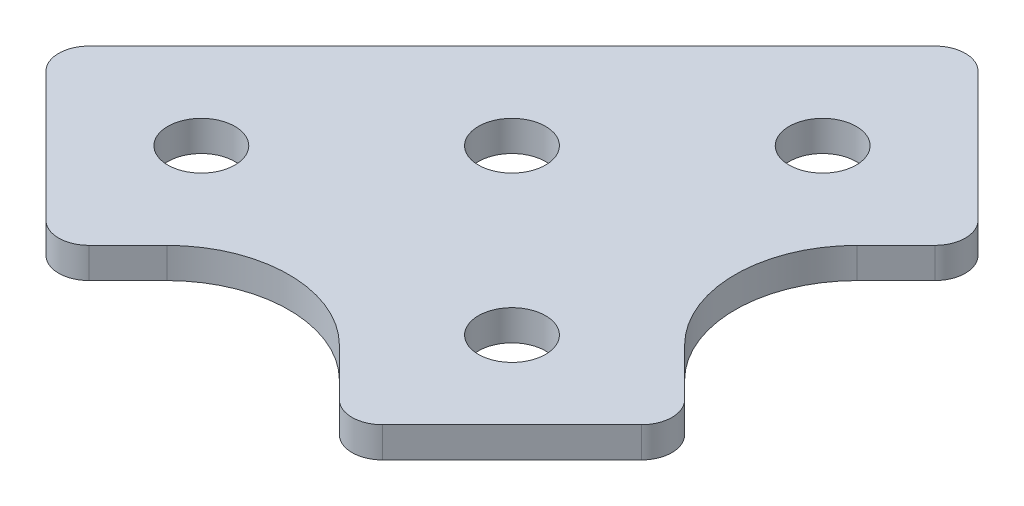
SolidWorks part; units mm, degrees
material "5052-H32"
ref_plane "Front Plane" through (0, 0, 0) normal (0, 0, 1) x (1, 0, 0)
ref_plane "Top Plane" through (0, 0, 0) normal (0, 1, 0) x (1, 0, 0)
ref_plane "Right Plane" through (0, 0, 0) normal (1, 0, 0) x (0, 0, -1)
sketch "Sketch1" plane through (0, 0, 0) normal (0, 1, 0) x (1, 0, 0)
  line L0 (-17.9605, 17.9605) -> (0, 35.921)
  line L5 (32.3289, -32.3289) -> (0, 0)
  line L6 (32.3289, -32.3289) -> (50.2894, -14.3684)
  line L7 (50.2894, -14.3684) -> (17.9605, 17.9605)
  line L9 (0, 0) -> (-31.4309, -31.4309)
  line L11 (-17.9605, 17.9605) -> (-49.3914, -13.4704)
  line L12 (-31.4309, -31.4309) -> (-49.3914, -13.4704)
  line L13 (0, 35.921) -> (17.9605, 17.9605)
  line L14 (-17.9605, 17.9605) -> (0, 0) construction
  line L15 (17.9605, 17.9605) -> (0, 0) construction
  line L16 (0, 0) -> (0, 35.921) construction
  point P3 (0, 17.9605)
  dimension "D1" = 25.4
  dimension "D2" = 25.4
  dimension "D5" = 90
  dimension "D4" = 45.72
  dimension "D3" = 57.15
extrude "Boss-Extrude1" add sketch "Sketch1" along normal blind 3.175 contours L0 L13 L7 L6 L5 L9 L12 L11
sketch "Sketch2" plane through (0, 3.175, 0) normal (0, 1, 0) x (1, 0, 0)
  line L0 (-49.3914, -13.4704) -> (-31.4309, -31.4309) construction
  line L1 (-32.3289, -14.3684) -> (-40.4112, -22.4506) construction
  line L2 (50.2894, -14.3684) -> (32.3289, -32.3289) construction
  line L3 (33.2269, -15.2664) -> (41.3092, -23.3487) construction
  circle A0 centre (-32.3289, -14.3684) radius 3.4925
  circle A1 centre (33.2269, -15.2664) radius 3.4925
  dimension "D1" = 6.985
  dimension "D2" = 11.43
sketch "Sketch7" plane through (0, 3.175, 0) normal (0, 1, 0) x (1, 0, 0)
  line L0 (-49.3914, -13.4704) -> (-31.4309, -31.4309) construction
  line L1 (-32.3289, -14.3684) -> (-40.4112, -22.4506) construction
  line L2 (50.2894, -14.3684) -> (32.3289, -32.3289) construction
  line L3 (33.2269, -15.2664) -> (41.3092, -23.3487) construction
  circle A0 centre (-32.3289, -14.3684) radius 3.4925
  circle A1 centre (33.2269, -15.2664) radius 3.4925
  dimension "D1" = 6.985
  dimension "D2" = 11.43
extrude "Cut-Extrude2" cut sketch "Sketch2" against normal blind 3.175 contours A0
pattern_linear "LPattern5" count 3 spacing 22.86 along (0.7071, 0, -0.7071) of "Cut-Extrude2"
extrude "Cut-Extrude3" cut sketch "Sketch7" against normal blind 3.175 contours A1
pattern_linear "LPattern6" count 2 spacing 22.86 along (-0.7071, 0, -0.7071) of "Cut-Extrude3"
ref_plane "Plane1" through (8.9803, 0, -8.9803) normal (-0.7071, 0, 0.7071) x (0.7071, 0, 0.7071)
mirror "Mirror2" about plane through (8.9803, 0, -8.9803) normal (-0.7071, 0, 0.7071) of bodies 107
sketch "Sketch8" plane through (0, 3.175, 0) normal (0, 1, 0) x (1, 0, 0)
  line L0 (49.3914, 49.3914) -> (31.4309, 67.3519) construction
  line L1 (-31.4309, -31.4309) -> (-49.3914, -13.4704) construction
  line L2 (49.3914, 49.3914) -> (31.4309, 67.3519)
  line L3 (-31.4309, -31.4309) -> (-49.3914, -13.4704)
  line L4 (-49.3914, -13.4704) -> (-31.4309, -31.4309)
  line L5 (-49.3914, -13.4704) -> (-33.2269, 2.6941)
  line L6 (-31.4309, -31.4309) -> (-15.2664, -15.2664)
  line L7 (-33.2269, 2.6941) -> (-15.2664, -15.2664)
  line L8 (31.4309, 67.3519) -> (49.3914, 49.3914)
  line L9 (31.4309, 67.3519) -> (15.2664, 51.1875)
  line L10 (49.3914, 49.3914) -> (33.2269, 33.2269)
  line L11 (15.2664, 51.1875) -> (33.2269, 33.2269)
  line L12 (32.3289, -32.3289) -> (50.2894, -14.3684) construction
  line L13 (32.3289, -32.3289) -> (50.2894, -14.3684)
  line L14 (32.3289, -32.3289) -> (50.2894, -14.3684)
  line L15 (32.3289, -32.3289) -> (16.1645, -16.1645)
  line L16 (50.2894, -14.3684) -> (34.125, 1.7961)
  line L17 (16.1645, -16.1645) -> (34.125, 1.7961)
  circle M7 centre (-32.3289, -14.3684) radius 3.4925
  line M8 (-31.4309, -31.4309) -> (0, 0)
  line M10 (0, 0) -> (32.3289, -32.3289)
  line M11 (32.3289, -32.3289) -> (50.2894, -14.3684)
  line M12 (50.2894, -14.3684) -> (17.9605, 17.9605)
  line M14 (17.9605, 17.9605) -> (49.3914, 49.3914)
  line M15 (49.3914, 49.3914) -> (31.4309, 67.3519)
  line M16 (31.4309, 67.3519) -> (-49.3914, -13.4704)
  line M17 (-49.3914, -13.4704) -> (-31.4309, -31.4309)
  circle M19 centre (33.2269, -15.2664) radius 3.4925
  circle M22 centre (32.3289, 50.2894) radius 3.4925
  dimension "D1" = 22.86
extrude "Cut-Extrude4" cut sketch "Sketch8" against normal through all contours L7 M16 M17 M8 M7 | L11 M16 M14 M15 M22 | L17 M10 M11 M12 M19
fillet "Fillet3" radius 12.7 2 edges at (17.9605, 1.5875, -17.9605) (0, 1.5875, 0)
fillet "Fillet4" radius 3.175 6 edges at (15.2664, 1.5875, -51.1875) (33.2269, 1.5875, -33.2269) (-33.2269, 1.5875, -2.6941) (-15.2664, 1.5875, 15.2664) (34.125, 1.5875, -1.7961) (16.1645, 1.5875, 16.1645)
equation "\"InnerAngle\"= 90"
equation "\"StockThickness\"= .125in"
equation "\"HoleDiameter\"= .275in"
equation "\"BarWidth\"= 1in"
equation "\"HoleSpacing\"=0.9"
equation "\"AdditionalHoleCount\"= 2"
equation "\"D1@Sketch1\"=\"BarWidth\""
equation "\"D2@Sketch1\"= \"BarWidth\""
equation "\"WingLength\"= ( \"AdditionalHoleCount\" ) * \"HoleSpacing\""
equation "\"D5@Sketch1\"=\"InnerAngle\""
equation "\"D1@Boss-Extrude1\"=\"StockThickness\""
equation "\"D1@Sketch2\"=\"HoleDiameter\""
equation "\"D2@Sketch2\"=\"HoleSpacing\"/2"
equation "\"D3@LPattern5\"=\"HoleSpacing\""
equation "\"D1@LPattern5\"=\"AdditionalHoleCount\"+1"
equation "\"D2@Sketch7\"=\"HoleSpacing\"/2"
equation "\"D1@Sketch7\"=\"HoleDiameter\""
equation "\"D3@LPattern6\"=\"HoleSpacing\""
equation "\"D1@LPattern6\"=\"AdditionalHoleCount\""
equation "\"D4@Sketch1\"=\"WingLength\""
equation "\"D3@Sketch1\"=\"WingLength\"+\"HoleSpacing\"/2"
